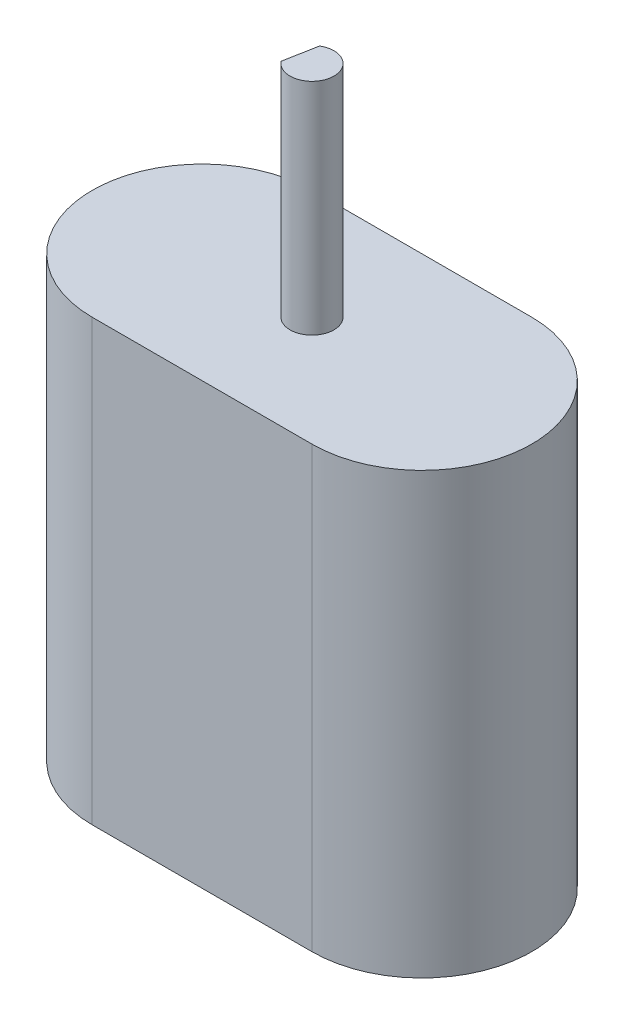
SolidWorks part; units mm, degrees
ref_plane "Front Plane" through (0, 0, 0) normal (0, 0, 1) x (1, 0, 0)
ref_plane "Top Plane" through (0, 0, 0) normal (0, 1, 0) x (1, 0, 0)
ref_plane "Right Plane" through (0, 0, 0) normal (1, 0, 0) x (0, 0, -1)
sketch "Sketch1" plane through (0, 0, 0) normal (0, 1, 0) x (1, 0, 0)
  line L0 (0, 0) -> (10, 0) construction
  line L5 (0, 5) -> (10, 5)
  line L6 (0, -5) -> (10, -5)
  arc A0 (0, 5) -> (0, -5) centre (0, 0) ccw
  arc A1 (10, -5) -> (10, 5) centre (10, 0) ccw
  point P2 (5, 0)
  point P9 (0, 0)
  point P10 (0, 0)
  point P11 (3.3846, 2.6154)
  dimension "D1" = 10
  dimension "D2" = 10
extrude "Boss-Extrude1" add sketch "Sketch1" along normal blind 20
sketch "Sketch2" plane through (0, 20, 0) normal (0, 1, 0) x (1, 0, 0)
  line L0 (0, 0) -> (10, 0) construction
  line L1 (5, 5) -> (5, -5) construction
  line L2 (10, 5) -> (0, 5) construction
  line L3 (0, -5) -> (10, -5) construction
  point P10 (5, 0)
sketch "Sketch4" plane through (0, 20, 0) normal (0, 1, 0) x (1, 0, 0)
  line L0 (5, 5) -> (5, -5) construction
  circle A0 centre (5, 0) radius 1
  dimension "D1" = 2
extrude "Boss-Extrude2" add sketch "Sketch4" along normal blind 10
sketch "Sketch5" plane through (0, 30, 0) normal (0, 1, 0) x (1, 0, 0)
  line L0 (4.4885, 0.8593) -> (4.2114, -0.6149)
  arc A0 (4.2114, -0.6149) -> (4.4885, 0.8593) centre (5, 0) cw
  circle A1 centre (5, 0) radius 1 construction
  dimension "D2" = 1
  dimension "D1" = 1.5
extrude "Cut-Extrude1" cut sketch "Sketch5" against normal blind 10
